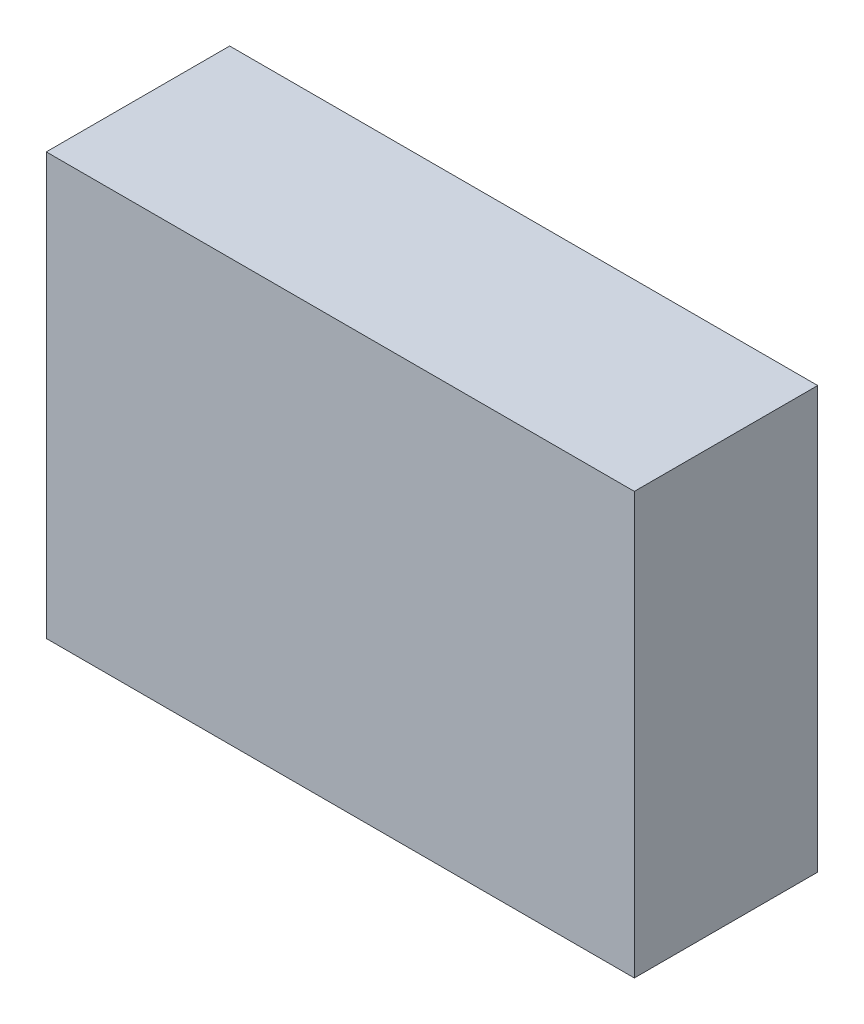
SolidWorks part; units mm, degrees
material "硅"
ref_plane "前视基准面" through (0, 0, 0) normal (0, 0, 1) x (1, 0, 0)
ref_plane "上视基准面" through (0, 0, 0) normal (0, 1, 0) x (1, 0, 0)
ref_plane "右视基准面" through (0, 0, 0) normal (1, 0, 0) x (0, 0, -1)
sketch "草图1" plane through (0, 0, 0) normal (0, 0, 1) x (1, 0, 0)
  line L1 (8.0171, -5.7456) -> (-8.0171, -5.7456)
  line L2 (8.0171, -5.7456) -> (8.0171, 5.7456)
  line L3 (8.0171, 5.7456) -> (-8.0171, 5.7456)
  line L4 (-8.0171, -5.7456) -> (-8.0171, 5.7456)
  line L5 (8.0171, -5.7456) -> (-8.0171, 5.7456) construction
  line L6 (8.0171, 5.7456) -> (-8.0171, -5.7456) construction
  point P0 (0, 0)
extrude "凸台-拉伸1" add sketch "草图1" along normal blind 5
